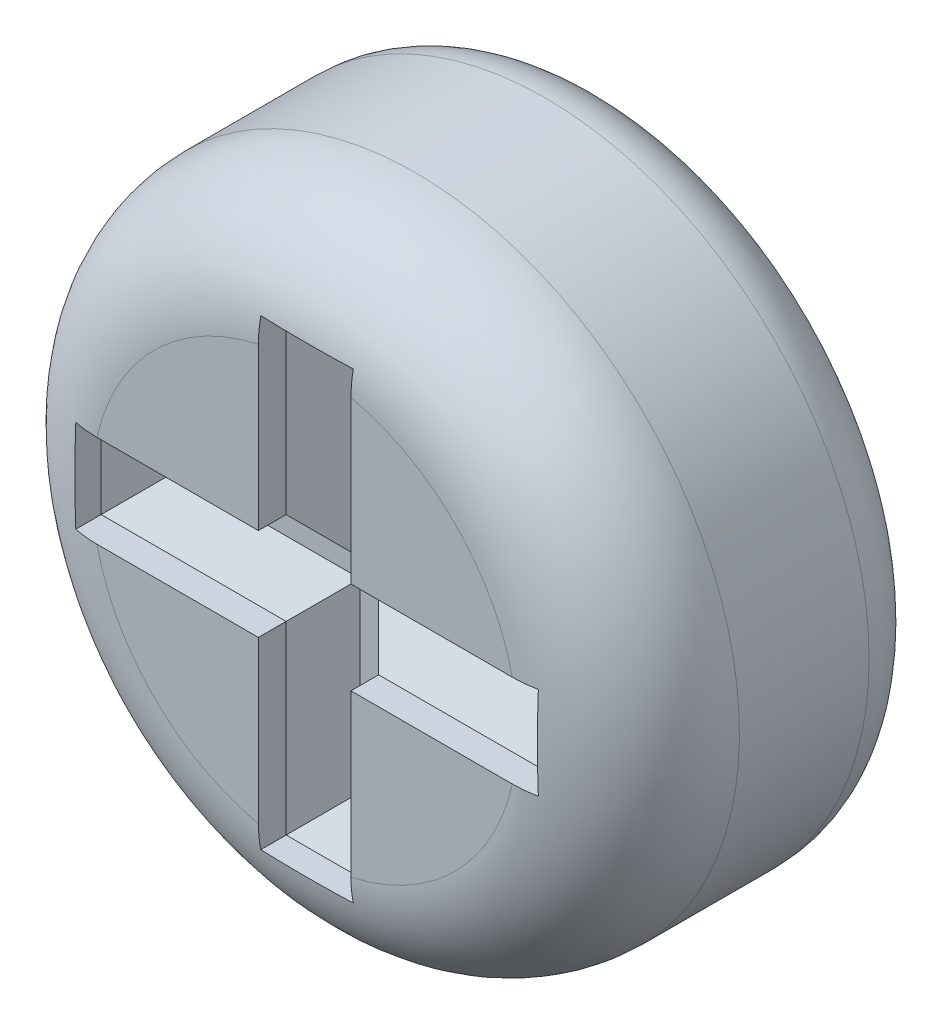
SolidWorks part; units mm, degrees
ref_plane "Front" through (0, 0, 0) normal (0, 0, 1) x (1, 0, 0)
ref_plane "Top" through (0, 0, 0) normal (0, 1, 0) x (1, 0, 0)
ref_plane "Right" through (0, 0, 0) normal (1, 0, 0) x (0, 0, -1)
sketch "Sketch1" plane through (0, 0, 0) normal (0, 0, 1) x (1, 0, 0)
  circle A0 centre (0, 0) radius 1.75
  dimension "D1" = 3.5
extrude "Extrude1" add sketch "Sketch1" along normal blind 1.651
fillet "Fillet1" radius 0.6
sketch "Sketch2" plane through (0, 0, 1.651) normal (0, 0, 1) x (1, 0, 0)
  line L0 (0.25, -0.25) -> (0.25, -1.25)
  line L1 (-0.25, 1.25) -> (0.25, 1.25)
  line L2 (-0.25, 1.25) -> (-0.25, 0.25)
  line L3 (-0.25, -1.25) -> (0.25, -1.25)
  line L4 (0.25, 1.25) -> (0.25, 0.25)
  line L5 (-1.25, 0.25) -> (-0.25, 0.25)
  line L6 (-1.25, 0.25) -> (-1.25, -0.25)
  line L7 (-1.25, -0.25) -> (-0.25, -0.25)
  line L8 (1.25, 0.25) -> (1.25, -0.25)
  line L9 (0.25, 0.25) -> (1.25, 0.25)
  line L10 (-0.25, -0.25) -> (-0.25, -1.25)
  line L11 (0.25, -0.25) -> (1.25, -0.25)
  dimension "D1" = 1.25
  dimension "D2" = 2.5
  dimension "D3" = 1.25
  dimension "D4" = 2.5
  dimension "D5" = 0.5
  dimension "D6" = 0.25
  dimension "D7" = 0.25
  dimension "D8" = 0.5
extrude "Cut-Extrude2" cut sketch "Sketch2" against normal blind 0.35
chamfer "Chamfer1" distance 0.2 angle 45
fillet "Fillet2" radius 0.35
